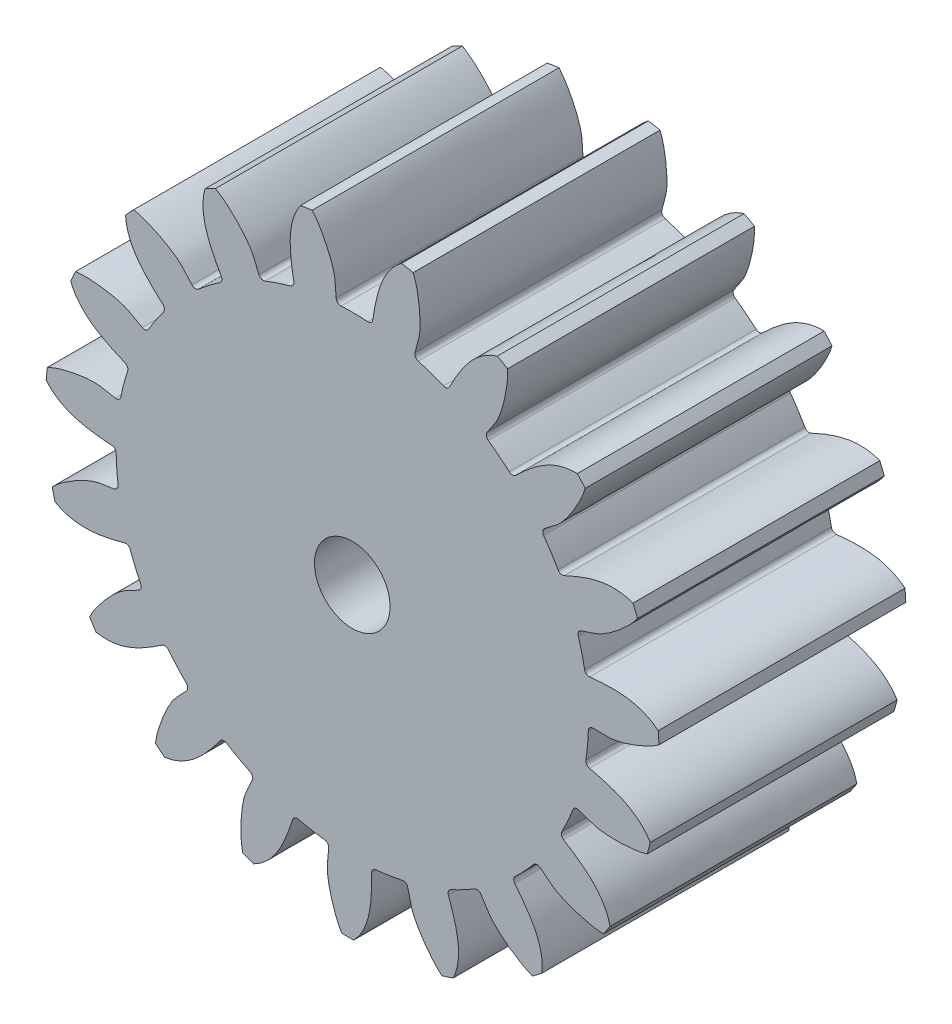
SolidWorks part; units mm, degrees
ref_plane "前视基准面" through (0, 0, 0) normal (0, 0, 1) x (1, 0, 0)
ref_plane "上视基准面" through (0, 0, 0) normal (0, 1, 0) x (1, 0, 0)
ref_plane "右视基准面" through (0, 0, 0) normal (1, 0, 0) x (0, 0, -1)
other "Configuration Table"
sketch "草图3" plane through (0, 0, 0) normal (0, 0, 1) x (1, 0, 0)
  circle A0 centre (0, 0) radius 13
  circle A1 centre (0, 0) radius 10
  dimension "D1" = 26
  dimension "D2" = 20
extrude "凸台-拉伸1" add sketch "草图3" along normal blind 4 contours A1 | A0 A1
sketch "草图6" plane through (0, 0, 4) normal (0, 0, 1) x (1, 0, 0)
  line L0 (0, 14.519) -> (0, -0.3622) construction
  line L5 (0, 0) -> (-1.6968, 12.8888) construction
  line L6 (-1.6968, 12.8888) -> (-1.8736, 14.2316)
  line L7 (-1.8736, 14.2316) -> (3.0009, 14.404)
  line L8 (3.0009, 14.404) -> (2.085, 12.8317)
  arc A0 (0.6559, 9.9785) -> (-0.4764, 9.9886) centre (0, 0) ccw
  circle A1 centre (0, 0) radius 13 construction
  arc A2 (0.6559, 9.9785) -> (0.8668, 10.1484) centre (0.669, 10.178) ccw
  arc A3 (-0.6854, 10.1744) -> (-0.4764, 9.9886) centre (-0.4859, 10.1884) ccw
  spline S0 degree 3 poles (-1.6968, 12.8888) (-1.3404, 12.4914) (-0.7219, 11.2236) (-0.7215, 10.6885) (-0.6854, 10.1744) knots 0 0 0 0 0.644244 0.940775 0.940775 0.940775 0.940775
  spline S1 degree 3 poles (2.085, 12.8317) (1.4718, 12.3854) (1.0735, 11.4242) (0.9081, 10.424) (0.8668, 10.1484) knots 0 0 0 0 0.67612 0.940775 0.940775 0.940775 0.940775
  dimension "D1" = 20
  dimension "D2" = 0.2
  dimension "D3" = 7.5
extrude "切除-拉伸2" cut sketch "草图6" against normal through all both
pattern_circular "阵列(圆周)4" count 19 every 18.947 about axis through (0, 0, 4) along (0, 0, 1) of "切除-拉伸2"
sketch "草图7" plane through (0, 0, 4) normal (0, 0, 1) x (1, 0, 0)
  circle A0 centre (0, 0) radius 12.5
  dimension "D1" = 25
ref_plane "基准面3" through (0, 0, 2) normal (0, 0, 1) x (1, 0, 0)
sketch "草图8" plane through (0, 0, 0) normal (0, 0, -1) x (-1, 0, 0)
  circle A5 centre (0, 0) radius 4.05
  dimension "D1" = 8.1
extrude "切除-拉伸4" cut sketch "草图8" against normal through all both
sketch "草图10" plane through (0, 0, 0) normal (0, 0, -1) x (-1, 0, 0)
  circle A0 centre (0, 0) radius 4.5
  dimension "D1" = 9
extrude "切除-拉伸5" cut sketch "草图10" against normal blind 0.6
sketch "草图11" plane through (0, 0, 4) normal (0, 0, 1) x (1, 0, 0)
  circle A0 centre (0, 0) radius 4.5
  dimension "D1" = 9
extrude "切除-拉伸6" cut sketch "草图11" against normal blind 0.6
sketch "草图13" plane through (0, 0, 4) normal (0, 0, 1) x (1, 0, 0)
  arc A61 (0.9955, -9.9503) -> (0.8154, -10.1526) centre (1.0154, -10.1493) ccw
  arc A62 (3.7951, -12.4337) -> (4.2735, -12.2775) centre (0, 0) ccw
  arc A63 (7.6267, -10.5277) -> (8.0285, -10.2247) centre (0, 0) ccw
  arc A64 (10.6318, -7.4809) -> (10.9134, -7.0638) centre (0, 0) ccw
  arc A65 (10.6318, -7.4809) -> (10.9134, -7.0638) centre (0, 0) ccw
  arc A66 (8.8746, -4.6089) -> (8.9454, -4.8703) centre (9.052, -4.7011) ccw
  arc A67 (8.8746, -4.6089) -> (8.9454, -4.8703) centre (9.052, -4.7011) ccw
  arc A68 (9.6948, 3.1621) -> (9.566, 2.9139) centre (9.7574, 2.9722) ccw
  arc A69 (12.0778, 4.8089) -> (11.8827, 5.2728) centre (0, 0) ccw
  arc A70 (8.7124, 4.9086) -> (8.97, 4.825) centre (8.8866, 5.0068) ccw
  arc A71 (8.7124, 4.9086) -> (8.1016, 5.8621) centre (0, 0) ccw
  arc A72 (8.1428, 6.1387) -> (8.1016, 5.8621) centre (8.2636, 5.9793) ccw
  arc A73 (9.862, 8.47) -> (9.5268, 8.8454) centre (0, 0) ccw
  arc A74 (6.6465, 7.4716) -> (6.9173, 7.4761) centre (6.7794, 7.621) ccw
  arc A75 (6.6465, 7.4716) -> (5.7592, 8.1751) centre (0, 0) ccw
  arc A76 (5.7084, 8.4501) -> (5.7592, 8.1751) centre (5.8744, 8.3386) ccw
  arc A77 (6.5774, 11.2133) -> (6.1385, 11.4595) centre (0, 0) ccw
  arc A78 (3.8603, 9.2248) -> (4.115, 9.3171) centre (3.9375, 9.4093) ccw
  arc A79 (3.8603, 9.2248) -> (2.7927, 9.6021) centre (0, 0) ccw
  arc A80 (2.6553, 9.8457) -> (2.7927, 9.6021) centre (2.8486, 9.7942) ccw
  arc A81 (2.5801, 12.7414) -> (2.085, 12.8317) centre (0, 0) ccw
  arc A82 (0.6559, 9.9785) -> (0.8668, 10.1484) centre (0.669, 10.178) ccw
  arc A83 (0.6559, 9.9785) -> (-0.4764, 9.9886) centre (0, 0) ccw
  arc A84 (-0.6854, 10.1744) -> (-0.4764, 9.9886) centre (-0.4859, 10.1884) ccw
  arc A85 (-1.6968, 12.8888) -> (-2.1944, 12.8134) centre (0, 0) ccw
  arc A86 (-2.6197, 9.6508) -> (-2.4754, 9.88) centre (-2.6721, 9.8438) ccw
  arc A87 (-2.6197, 9.6508) -> (-3.6939, 9.2927) centre (0, 0) ccw
  arc A88 (-3.9519, 9.4006) -> (-3.6939, 9.2927) centre (-3.7678, 9.4786) ccw
  arc A89 (-5.7899, 11.6395) -> (-6.236, 11.4067) centre (0, 0) ccw
  arc A90 (-5.6113, 8.2773) -> (-5.5493, 8.5409) centre (-5.7236, 8.4428) ccw
  arc A91 (-5.6113, 8.2773) -> (-6.5111, 7.5898) centre (0, 0) ccw
  arc A92 (-6.7902, 7.608) -> (-6.5111, 7.5898) centre (-6.6413, 7.7416) ccw
  arc A93 (-9.2555, 9.1288) -> (-9.6019, 8.7638) centre (0, 0) ccw
  arc A94 (-7.9949, 6.0068) -> (-8.0218, 6.2763) centre (-8.1548, 6.1269) ccw
  arc A95 (-7.9949, 6.0068) -> (-8.6227, 5.0644) centre (0, 0) ccw
  arc A96 (-8.8926, 4.9911) -> (-8.6227, 5.0644) centre (-8.7952, 5.1657) ccw
  arc A97 (-11.7181, 5.629) -> (-11.9272, 5.1712) centre (0, 0) ccw
  arc A98 (-9.5121, 3.0854) -> (-9.6251, 3.3315) centre (-9.7024, 3.1471) ccw
  arc A99 (-9.5121, 3.0854) -> (-9.7999, 1.9902) centre (0, 0) ccw
  arc A100 (-10.0314, 1.8332) -> (-9.7999, 1.9902) centre (-9.9959, 2.03) ccw
  arc A101 (-12.9109, 1.5191) -> (-12.9601, 1.0182) centre (0, 0) ccw
  arc A102 (-9.9985, -0.1704) -> (-10.1853, 0.0258) centre (-10.1985, -0.1738) ccw
  arc A103 (-9.9985, -0.1704) -> (-9.9152, -1.2996) centre (0, 0) ccw
  arc A104 (-10.0831, -1.5233) -> (-9.9152, -1.2996) centre (-10.1135, -1.3256) ccw
  arc A105 (-12.7046, -2.7554) -> (-12.5885, -3.2451) centre (0, 0) ccw
  arc A106 (-9.4015, -3.4077) -> (-9.6418, -3.2828) centre (-9.5895, -3.4758) ccw
  arc A107 (-9.4015, -3.4077) -> (-8.956, -4.4487) centre (0, 0) ccw
  arc A108 (-9.0421, -4.7147) -> (-8.956, -4.4487) centre (-9.1351, -4.5376) ccw
  arc A109 (-11.1216, -6.7313) -> (-10.8527, -7.1567) centre (0, 0) ccw
  arc A110 (-7.7856, -6.2757) -> (-8.0535, -6.2356) centre (-7.9413, -6.4012) ccw
  arc A111 (-7.7856, -6.2757) -> (-7.0262, -7.1156) centre (0, 0) ccw
  arc A112 (-7.0213, -7.3953) -> (-7.0262, -7.1156) centre (-7.1667, -7.2579) ccw
  arc A113 (-8.3333, -9.9777) -> (-7.9409, -10.2928) centre (0, 0) ccw
  arc A114 (-5.326, -8.4636) -> (-5.5924, -8.5127) centre (-5.4326, -8.6329) ccw
  arc A115 (-5.326, -8.4636) -> (-4.3351, -9.0115) centre (0, 0) ccw
  arc A116 (-4.2397, -9.2744) -> (-4.3351, -9.0115) centre (-4.4218, -9.1917) ccw
  arc A117 (-4.6421, -12.143) -> (-4.1686, -12.3135) centre (0, 0) ccw
  arc A118 (-2.2893, -9.7344) -> (-2.5253, -9.8673) centre (-2.3351, -9.9291) ccw
  arc A119 (-2.2893, -9.7344) -> (-1.1742, -9.9308) centre (0, 0) ccw
  arc A120 (-0.9986, -10.1485) -> (-1.1742, -9.9308) centre (-1.1976, -10.1294) ccw
  arc A121 (-0.4477, -12.9923) -> (0.0555, -12.9999) centre (0, 0) ccw
  arc A122 (0.9955, -9.9503) -> (0.8154, -10.1526) centre (1.0154, -10.1493) ccw
  arc A123 (3.7951, -12.4337) -> (4.2735, -12.2775) centre (0, 0) ccw
  arc A124 (7.6267, -10.5277) -> (8.0285, -10.2247) centre (0, 0) ccw
  arc A129 (9.6948, 3.1621) -> (9.566, 2.9139) centre (9.7574, 2.9722) ccw
  arc A130 (12.0778, 4.8089) -> (11.8827, 5.2728) centre (0, 0) ccw
  arc A131 (8.7124, 4.9086) -> (8.97, 4.825) centre (8.8866, 5.0068) ccw
  arc A132 (8.7124, 4.9086) -> (8.1016, 5.8621) centre (0, 0) ccw
  arc A133 (8.1428, 6.1387) -> (8.1016, 5.8621) centre (8.2636, 5.9793) ccw
  arc A134 (9.862, 8.47) -> (9.5268, 8.8454) centre (0, 0) ccw
  arc A135 (6.6465, 7.4716) -> (6.9173, 7.4761) centre (6.7794, 7.621) ccw
  arc A136 (6.6465, 7.4716) -> (5.7592, 8.1751) centre (0, 0) ccw
  arc A137 (5.7084, 8.4501) -> (5.7592, 8.1751) centre (5.8744, 8.3386) ccw
  arc A138 (6.5774, 11.2133) -> (6.1385, 11.4595) centre (0, 0) ccw
  arc A139 (3.8603, 9.2248) -> (4.115, 9.3171) centre (3.9375, 9.4093) ccw
  arc A140 (3.8603, 9.2248) -> (2.7927, 9.6021) centre (0, 0) ccw
  arc A141 (2.6553, 9.8457) -> (2.7927, 9.6021) centre (2.8486, 9.7942) ccw
  arc A142 (2.5801, 12.7414) -> (2.085, 12.8317) centre (0, 0) ccw
  arc A143 (0.6559, 9.9785) -> (0.8668, 10.1484) centre (0.669, 10.178) ccw
  arc A144 (0.6559, 9.9785) -> (-0.4764, 9.9886) centre (0, 0) ccw
  arc A145 (-0.6854, 10.1744) -> (-0.4764, 9.9886) centre (-0.4859, 10.1884) ccw
  arc A146 (-1.6968, 12.8888) -> (-2.1944, 12.8134) centre (0, 0) ccw
  arc A147 (-2.6197, 9.6508) -> (-2.4754, 9.88) centre (-2.6721, 9.8438) ccw
  arc A148 (-2.6197, 9.6508) -> (-3.6939, 9.2927) centre (0, 0) ccw
  arc A149 (-3.9519, 9.4006) -> (-3.6939, 9.2927) centre (-3.7678, 9.4786) ccw
  arc A150 (-5.7899, 11.6395) -> (-6.236, 11.4067) centre (0, 0) ccw
  arc A151 (-5.6113, 8.2773) -> (-5.5493, 8.5409) centre (-5.7236, 8.4428) ccw
  arc A152 (-5.6113, 8.2773) -> (-6.5111, 7.5898) centre (0, 0) ccw
  arc A153 (-6.7902, 7.608) -> (-6.5111, 7.5898) centre (-6.6413, 7.7416) ccw
  arc A154 (-9.2555, 9.1288) -> (-9.6019, 8.7638) centre (0, 0) ccw
  arc A155 (-7.9949, 6.0068) -> (-8.0218, 6.2763) centre (-8.1548, 6.1269) ccw
  arc A156 (-7.9949, 6.0068) -> (-8.6227, 5.0644) centre (0, 0) ccw
  arc A157 (-8.8926, 4.9911) -> (-8.6227, 5.0644) centre (-8.7952, 5.1657) ccw
  arc A158 (-11.7181, 5.629) -> (-11.9272, 5.1712) centre (0, 0) ccw
  arc A159 (-9.5121, 3.0854) -> (-9.6251, 3.3315) centre (-9.7024, 3.1471) ccw
  arc A160 (-9.5121, 3.0854) -> (-9.7999, 1.9902) centre (0, 0) ccw
  arc A161 (-10.0314, 1.8332) -> (-9.7999, 1.9902) centre (-9.9959, 2.03) ccw
  arc A162 (-12.9109, 1.5191) -> (-12.9601, 1.0182) centre (0, 0) ccw
  arc A163 (-9.9985, -0.1704) -> (-10.1853, 0.0258) centre (-10.1985, -0.1738) ccw
  arc A164 (-9.9985, -0.1704) -> (-9.9152, -1.2996) centre (0, 0) ccw
  arc A165 (-10.0831, -1.5233) -> (-9.9152, -1.2996) centre (-10.1135, -1.3256) ccw
  arc A166 (-12.7046, -2.7554) -> (-12.5885, -3.2451) centre (0, 0) ccw
  arc A167 (-9.4015, -3.4077) -> (-9.6418, -3.2828) centre (-9.5895, -3.4758) ccw
  arc A168 (-9.4015, -3.4077) -> (-8.956, -4.4487) centre (0, 0) ccw
  arc A169 (-9.0421, -4.7147) -> (-8.956, -4.4487) centre (-9.1351, -4.5376) ccw
  arc A170 (-11.1216, -6.7313) -> (-10.8527, -7.1567) centre (0, 0) ccw
  arc A171 (-7.7856, -6.2757) -> (-8.0535, -6.2356) centre (-7.9413, -6.4012) ccw
  arc A172 (-7.7856, -6.2757) -> (-7.0262, -7.1156) centre (0, 0) ccw
  arc A173 (-7.0213, -7.3953) -> (-7.0262, -7.1156) centre (-7.1667, -7.2579) ccw
  arc A174 (-8.3333, -9.9777) -> (-7.9409, -10.2928) centre (0, 0) ccw
  arc A175 (-5.326, -8.4636) -> (-5.5924, -8.5127) centre (-5.4326, -8.6329) ccw
  arc A176 (-5.326, -8.4636) -> (-4.3351, -9.0115) centre (0, 0) ccw
  arc A177 (-4.2397, -9.2744) -> (-4.3351, -9.0115) centre (-4.4218, -9.1917) ccw
  arc A178 (-4.6421, -12.143) -> (-4.1686, -12.3135) centre (0, 0) ccw
  arc A179 (-2.2893, -9.7344) -> (-2.5253, -9.8673) centre (-2.3351, -9.9291) ccw
  arc A180 (-2.2893, -9.7344) -> (-1.1742, -9.9308) centre (0, 0) ccw
  arc A181 (-0.9986, -10.1485) -> (-1.1742, -9.9308) centre (-1.1976, -10.1294) ccw
  arc A182 (-0.4477, -12.9923) -> (0.0555, -12.9999) centre (0, 0) ccw
  arc A198 (8.8746, -4.6089) -> (9.3387, -3.5761) centre (0, 0) ccw
  arc A199 (8.8746, -4.6089) -> (9.3387, -3.5761) centre (0, 0) ccw
  arc A200 (9.5928, -3.4593) -> (9.3387, -3.5761) centre (9.5255, -3.6476) ccw
  arc A201 (9.5928, -3.4593) -> (9.3387, -3.5761) centre (9.5255, -3.6476) ccw
  arc A202 (12.4848, -3.6234) -> (12.6157, -3.1375) centre (0, 0) ccw
  arc A203 (12.4848, -3.6234) -> (12.6157, -3.1375) centre (0, 0) ccw
  arc A204 (9.8902, -1.4776) -> (10.0421, -1.7019) centre (10.088, -1.5072) ccw
  arc A205 (9.8902, -1.4776) -> (10.0421, -1.7019) centre (10.088, -1.5072) ccw
  arc A206 (9.8902, -1.4776) -> (9.9939, -0.3501) centre (0, 0) ccw
  arc A207 (9.8902, -1.4776) -> (9.9939, -0.3501) centre (0, 0) ccw
  arc A208 (10.1963, -0.1571) -> (9.9939, -0.3501) centre (10.1937, -0.3571) ccw
  arc A209 (10.1963, -0.1571) -> (9.9939, -0.3501) centre (10.1937, -0.3571) ccw
  arc A210 (12.9849, 0.6267) -> (12.9509, 1.1288) centre (0, 0) ccw
  arc A211 (12.9849, 0.6267) -> (12.9509, 1.1288) centre (0, 0) ccw
  arc A212 (9.8341, 1.8138) -> (10.0506, 1.651) centre (10.0308, 1.85) ccw
  arc A213 (9.8341, 1.8138) -> (10.0506, 1.651) centre (10.0308, 1.85) ccw
  arc A214 (9.8341, 1.8138) -> (9.566, 2.9139) centre (0, 0) ccw
  arc A215 (9.8341, 1.8138) -> (9.566, 2.9139) centre (0, 0) ccw
  arc A216 (0.9955, -9.9503) -> (2.114, -9.774) centre (0, 0) ccw
  arc A217 (0.9955, -9.9503) -> (2.114, -9.774) centre (0, 0) ccw
  arc A218 (2.3508, -9.9228) -> (2.114, -9.774) centre (2.1563, -9.9695) ccw
  arc A219 (2.3508, -9.9228) -> (2.114, -9.774) centre (2.1563, -9.9695) ccw
  arc A220 (4.1724, -9.088) -> (4.0678, -9.3378) centre (4.2559, -9.2697) ccw
  arc A221 (4.1724, -9.088) -> (4.0678, -9.3378) centre (4.2559, -9.2697) ccw
  arc A222 (4.1724, -9.088) -> (5.1731, -8.558) centre (0, 0) ccw
  arc A223 (4.1724, -9.088) -> (5.1731, -8.558) centre (0, 0) ccw
  arc A224 (5.4453, -8.6219) -> (5.1731, -8.558) centre (5.2765, -8.7292) ccw
  arc A225 (5.4453, -8.6219) -> (5.1731, -8.558) centre (5.2765, -8.7292) ccw
  arc A226 (6.8972, -7.2408) -> (6.8794, -7.511) centre (7.0351, -7.3856) ccw
  arc A227 (6.8972, -7.2408) -> (6.8794, -7.511) centre (7.0351, -7.3856) ccw
  arc A228 (6.8972, -7.2408) -> (7.6715, -6.4146) centre (0, 0) ccw
  arc A229 (6.8972, -7.2408) -> (7.6715, -6.4146) centre (0, 0) ccw
  arc A230 (7.9498, -6.3867) -> (7.6715, -6.4146) centre (7.825, -6.5429) ccw
  arc A231 (7.9498, -6.3867) -> (7.6715, -6.4146) centre (7.825, -6.5429) ccw
  spline S31 degree 3 poles (-731.5328, 1850.5138) (19.8543, -20.677) (-32.4011, 17.1172) (72.329, -78.5631) (-1032.4895, 1698.0412) knots -4.705235 -4.705235 -4.705235 -4.705235 0.296531 9.087902 9.087902 9.087902 9.087902 only from (2.3508, -9.9228) to (3.7951, -12.4337)
  spline S32 degree 3 poles (-1919.6578, 532.6232) (-27.8786, -49.6134) (46.8106, 5.6607) (-49.9844, 2.209) (1993.0973, -217.6497) knots -11.806964 -11.806964 -11.806964 -11.806964 0.67612 14.264014 14.264014 14.264014 14.264014 only from (4.2735, -12.2775) to (4.0678, -9.3378)
  spline S33 degree 3 poles (-1292.7572, 1512.7195) (25.4924, -13.11) (-36.2034, 5.6691) (93.9194, -50.8212) (-1527.8994, 1270.7879) knots -4.705235 -4.705235 -4.705235 -4.705235 0.296531 9.087902 9.087902 9.087902 9.087902 only from (5.4453, -8.6219) to (7.6267, -10.5277)
  spline S34 degree 3 poles (-1783.7839, -881.8485) (18.9669, 21.494) (-14.3831, -33.7039) (72.3219, 78.5696) (-1606.9792, -1169.1861) knots -4.705235 -4.705235 -4.705235 -4.705235 0.296531 9.087902 9.087902 9.087902 9.087902 only from (9.6948, 3.1621) to (12.0778, 4.8089)
  spline S35 degree 3 poles (-372.2799, -1957.0849) (51.7462, -23.6864) (-9.507, 46.1833) (1.9262, -49.9961) (52.3177, 2004.2632) knots -11.806964 -11.806964 -11.806964 -11.806964 0.67612 14.264014 14.264014 14.264014 14.264014 only from (11.8827, 5.2728) to (8.97, 4.825)
  spline S36 degree 3 poles (-1400.7978, -1413.2612) (10.9601, 26.4879) (-2.6601, -36.5479) (42.8918, 97.7954) (-1140.2745, -1627.6217) knots -4.705235 -4.705235 -4.705235 -4.705235 0.296531 9.087902 9.087902 9.087902 9.087902 only from (8.1428, 6.1387) to (9.862, 8.47)
  spline S37 degree 3 poles (283.3557, -1971.9237) (56.6334, -5.601) (-23.9876, 40.594) (18.0555, -46.6618) (-601.3002, 1912.6542) knots -11.806964 -11.806964 -11.806964 -11.806964 0.67612 14.264014 14.264014 14.264014 14.264014 only from (9.5268, 8.8454) to (6.9173, 7.4761)
  spline S38 degree 3 poles (-866.0135, -1791.5251) (1.7656, 28.6115) (9.3511, -35.4314) (8.8137, 106.4235) (-550.0034, -1909.6792) knots -4.705235 -4.705235 -4.705235 -4.705235 0.296531 9.087902 9.087902 9.087902 9.087902 only from (5.7084, 8.4501) to (6.5774, 11.2133)
  spline S39 degree 3 poles (908.2853, -1773.074) (55.3835, 13.0913) (-35.8687, 30.6058) (32.2283, -38.2709) (-1189.7579, 1613.7795) knots -11.806964 -11.806964 -11.806964 -11.806964 0.67612 14.264014 14.264014 14.264014 14.264014 only from (6.1385, 11.4595) to (4.115, 9.3171)
  spline S40 degree 3 poles (-237.3833, -1975.6495) (-7.6202, 27.6345) (20.349, -30.4753) (-26.2195, 103.519) (99.8691, -1984.7933) knots -4.705235 -4.705235 -4.705235 -4.705235 0.296531 9.087902 9.087902 9.087902 9.087902 only from (2.6553, 9.8457) to (2.5801, 12.7414)
  spline S41 degree 3 poles (1434.7881, -1382.0843) (48.1319, 30.3649) (-43.8629, 17.3009) (42.9086, -25.7327) (-1649.2869, 1140.0267) knots -11.806964 -11.806964 -11.806964 -11.806964 0.67612 14.264014 14.264014 14.264014 14.264014 only from (2.085, 12.8317) to (0.8668, 10.1484)
  spline S42 degree 3 poles (416.9711, -1945.6816) (-16.1802, 23.6629) (29.1418, -22.2168) (-58.4114, 89.3966) (738.9193, -1844.8243) knots -4.705235 -4.705235 -4.705235 -4.705235 0.296531 9.087902 9.087902 9.087902 9.087902 only from (-0.6854, 10.1744) to (-1.6968, 12.8888)
  spline S43 degree 3 poles (1805.8093, -841.3242) (35.6645, 44.3481) (-47.1039, 2.1212) (48.9391, -10.4061) (-1930.0901, 542.7343) knots -11.806964 -11.806964 -11.806964 -11.806964 0.67612 14.264014 14.264014 14.264014 14.264014 only from (-2.1944, 12.8134) to (-2.4754, 9.88)
  spline S44 degree 3 poles (1026.1402, -1704.8689) (-22.9869, 17.1271) (34.7766, -11.5507) (-84.2736, 65.5867) (1297.8961, -1504.9399) knots -4.705235 -4.705235 -4.705235 -4.705235 0.296531 9.087902 9.087902 9.087902 9.087902 only from (-3.9519, 9.4006) to (-5.7899, 11.6395)
  spline S45 degree 3 poles (1981.1431, -209.3936) (19.3323, 53.5254) (-45.2404, -13.2883) (49.6663, 6.0482) (-2001.738, -113.3717) knots -11.806964 -11.806964 -11.806964 -11.806964 0.67612 14.264014 14.264014 14.264014 14.264014 only from (-6.236, 11.4067) to (-5.5493, 8.5409)
  spline S46 degree 3 poles (1524.1111, -1279.3072) (-27.3026, 8.7353) (36.6428, 0.3671) (-101.0033, 34.6694) (1716.2257, -1001.972) knots -4.705235 -4.705235 -4.705235 -4.705235 0.296531 9.087902 9.087902 9.087902 9.087902 only from (-6.7902, 7.608) to (-9.2555, 9.1288)
  spline S47 degree 3 poles (1941.7893, 445.228) (0.9051, 56.9025) (-38.4745, -27.2579) (45.0114, 21.8472) (-1856.4666, -757.1922) knots -11.806964 -11.806964 -11.806964 -11.806964 0.67612 14.264014 14.264014 14.264014 14.264014 only from (-9.6019, 8.7638) to (-8.0218, 6.2763)
  spline S48 degree 3 poles (1856.921, -715.1127) (-28.6596, -0.6031) (34.5382, 12.2451) (-106.7879, -0.0048) (1948.5756, -390.4248) knots -4.705235 -4.705235 -4.705235 -4.705235 0.296531 9.087902 9.087902 9.087902 9.087902 only from (-8.8926, 4.9911) to (-11.7181, 5.629)
  spline S49 degree 3 poles (1692.0125, 1051.6023) (-17.6201, 54.1132) (-27.5392, -38.2736) (35.4788, 35.2786) (-1510.0182, -1318.9592) knots -11.806964 -11.806964 -11.806964 -11.806964 0.67612 14.264014 14.264014 14.264014 14.264014 only from (-11.9272, 5.1712) to (-9.6251, 3.3315)
  spline S50 degree 3 poles (1988.5046, -73.4247) (-26.9109, -9.8762) (28.6908, 22.7962) (-101.0002, -34.6785) (1969.7671, 263.4309) knots -4.705235 -4.705235 -4.705235 -4.705235 0.296531 9.087902 9.087902 9.087902 9.087902 only from (-10.0314, 1.8332) to (-12.9109, 1.5191)
  spline S51 degree 3 poles (1258.8799, 1544.0191) (-34.2359, 45.46) (-13.6196, -45.1418) (22.1015, 44.887) (-999.9359, -1737.7964) knots -11.806964 -11.806964 -11.806964 -11.806964 0.67612 14.264014 14.264014 14.264014 14.264014 only from (-12.9601, 1.0182) to (-10.1853, 0.0258)
  spline S52 degree 3 poles (1904.6029, 576.2201) (-22.246, -18.079) (19.7344, 30.8769) (-84.2677, -65.5942) (1777.5038, 888.7399) knots -4.705235 -4.705235 -4.705235 -4.705235 0.296531 9.087902 9.087902 9.087902 9.087902 only from (-10.0831, -1.5233) to (-12.7046, -2.7554)
  spline S53 degree 3 poles (689.3281, 1869.1176) (-47.1418, 31.8805) (1.7758, -47.1182) (6.3292, 49.6313) (-381.495, -1968.3165) knots -11.806964 -11.806964 -11.806964 -11.806964 0.67612 14.264014 14.264014 14.264014 14.264014 only from (-12.5885, -3.2451) to (-9.6418, -3.2828)
  spline S54 degree 3 poles (1614.3079, 1163.4224) (-15.1704, -24.3227) (8.6394, 35.6116) (-58.4034, -89.4018) (1392.6204, 1417.74) knots -4.705235 -4.705235 -4.705235 -4.705235 0.296531 9.087902 9.087902 9.087902 9.087902 only from (-9.0421, -4.7147) to (-11.1216, -6.7313)
  spline S55 degree 3 poles (45.0769, 1991.6681) (-54.9391, 14.8462) (16.9789, -43.9886) (-10.129, 48.9972) (278.2867, -1985.5389) knots -11.806964 -11.806964 -11.806964 -11.806964 0.67612 14.264014 14.264014 14.264014 14.264014 only from (-10.8527, -7.1567) to (-8.0535, -6.2356)
  spline S56 degree 3 poles (1149.0776, 1624.5499) (-6.4508, -27.9307) (-3.3918, 36.4873) (-26.2102, -103.5214) (856.8249, 1793.1061) knots -4.705235 -4.705235 -4.705235 -4.705235 0.296531 9.087902 9.087902 9.087902 9.087902 only from (-7.0213, -7.3953) to (-8.3333, -9.9777)
  spline S57 degree 3 poles (-604.059, 1898.3905) (-56.7829, -3.7969) (30.342, -36.0921) (-25.4895, 43.0535) (907.9118, -1787.5973) knots -11.806964 -11.806964 -11.806964 -11.806964 0.67612 14.264014 14.264014 14.264014 14.264014 only from (-7.9409, -10.2928) to (-5.5924, -8.5127)
  spline S58 degree 3 poles (559.3269, 1909.6322) (2.9678, -28.5119) (-15.0554, 33.409) (8.8232, -106.4227) (228.1792, 1974.1613) knots -4.705235 -4.705235 -4.705235 -4.705235 0.296531 9.087902 9.087902 9.087902 9.087902 only from (-4.2397, -9.2744) to (-4.6421, -12.143)
  spline S59 degree 3 poles (-1187.7358, 1599.3928) (-52.4733, -22.0285) (40.417, -24.2845) (-38.0879, 32.4443) (1439.1506, -1395.9419) knots -11.806964 -11.806964 -11.806964 -11.806964 0.67612 14.264014 14.264014 14.264014 14.264014 only from (-4.1686, -12.3135) to (-2.5253, -9.8673)
  spline S60 degree 3 poles (-91.0355, 1987.7762) (12.0648, -26.0034) (-25.0876, 26.7103) (42.9006, -97.7916) (-425.1933, 1941.2854) knots -4.705235 -4.705235 -4.705235 -4.705235 0.296531 9.087902 9.087902 9.087902 9.087902 only from (-0.9986, -10.1485) to (-0.4477, -12.9923)
  spline S61 degree 3 poles (-1642.703, 1127.0761) (-42.4775, -37.8731) (46.1123, -9.8454) (-46.5588, 18.3193) (1814.435, -853.0145) knots -11.806964 -11.806964 -11.806964 -11.806964 0.67612 14.264014 14.264014 14.264014 14.264014 only from (0.0555, -12.9999) to (0.8154, -10.1526)
  spline S62 degree 3 poles (2.3508, -9.9228) (2.4709, -10.4239) (2.5593, -10.9517) (3.3781, -12.1004) (3.7951, -12.4337) knots 0 0 0 0 0.296531 0.940775 0.940775 0.940775 0.940775
  spline S63 degree 3 poles (4.2735, -12.2775) (4.6004, -11.5931) (4.4932, -10.5582) (4.1626, -9.5998) (4.0678, -9.3378) knots 0 0 0 0 0.67612 0.940775 0.940775 0.940775 0.940775
  spline S64 degree 3 poles (5.4453, -8.6219) (5.7217, -9.0568) (5.9767, -9.5273) (7.1241, -10.3479) (7.6267, -10.5277) knots 0 0 0 0 0.296531 0.940775 0.940775 0.940775 0.940775
  spline S65 degree 3 poles (9.6948, 3.1621) (10.1843, 3.3233) (10.7029, 3.455) (11.7801, 4.3658) (12.0778, 4.8089) knots 0 0 0 0 0.296531 0.940775 0.940775 0.940775 0.940775
  spline S66 degree 3 poles (11.8827, 5.2728) (11.1736, 5.5421) (10.1511, 5.3497) (9.2233, 4.9412) (8.97, 4.825) knots 0 0 0 0 0.67612 0.940775 0.940775 0.940775 0.940775
  spline S67 degree 3 poles (8.1428, 6.1387) (8.5534, 6.45) (9.0012, 6.743) (9.7242, 7.9542) (9.862, 8.47) knots 0 0 0 0 0.296531 0.940775 0.940775 0.940775 0.940775
  spline S68 degree 3 poles (9.5268, 8.8454) (8.7687, 8.8699) (7.8641, 8.3559) (7.1192, 7.6683) (6.9173, 7.4761) knots 0 0 0 0 0.67612 0.940775 0.940775 0.940775 0.940775
  spline S69 degree 3 poles (5.7084, 8.4501) (5.9956, 8.8778) (6.324, 9.3003) (6.6146, 10.6807) (6.5774, 11.2133) knots 0 0 0 0 0.296531 0.940775 0.940775 0.940775 0.940775
  spline S70 degree 3 poles (6.1385, 11.4595) (5.4135, 11.2365) (4.7248, 10.4567) (4.2436, 9.5644) (4.115, 9.3171) knots 0 0 0 0 0.67612 0.940775 0.940775 0.940775 0.940775
  spline S71 degree 3 poles (2.6553, 9.8457) (2.7881, 10.3436) (2.9615, 10.8498) (2.7882, 12.2498) (2.5801, 12.7414) knots 0 0 0 0 0.296531 0.940775 0.940775 0.940775 0.940775
  spline S72 degree 3 poles (2.085, 12.8317) (1.4718, 12.3854) (1.0735, 11.4242) (0.9081, 10.424) (0.8668, 10.1484) knots 0 0 0 0 0.67612 0.940775 0.940775 0.940775 0.940775
  spline S73 degree 3 poles (-0.6854, 10.1744) (-0.7215, 10.6885) (-0.7219, 11.2236) (-1.3404, 12.4914) (-1.6968, 12.8888) knots 0 0 0 0 0.296531 0.940775 0.940775 0.940775 0.940775
  spline S74 degree 3 poles (-2.1944, 12.8134) (-2.6295, 12.1922) (-2.6941, 11.1538) (-2.5258, 10.1541) (-2.4754, 9.88) knots 0 0 0 0 0.67612 0.940775 0.940775 0.940775 0.940775
  spline S75 degree 3 poles (-3.9519, 9.4006) (-4.1529, 9.8751) (-4.327, 10.3811) (-5.3237, 11.3793) (-5.7899, 11.6395) knots 0 0 0 0 0.296531 0.940775 0.940775 0.940775 0.940775
  spline S76 degree 3 poles (-6.236, 11.4067) (-6.4459, 10.6778) (-6.1697, 9.6747) (-5.6859, 8.7838) (-5.5493, 8.5409) knots 0 0 0 0 0.67612 0.940775 0.940775 0.940775 0.940775
  spline S77 degree 3 poles (-6.7902, 7.608) (-7.1343, 7.9916) (-7.4633, 8.4136) (-8.7301, 9.0342) (-9.2555, 9.1288) knots 0 0 0 0 0.296531 0.940775 0.940775 0.940775 0.940775
  spline S78 degree 3 poles (-9.6019, 8.7638) (-9.5637, 8.0063) (-8.9768, 7.1472) (-8.23, 6.4616) (-8.0218, 6.2763) knots 0 0 0 0 0.67612 0.940775 0.940775 0.940775 0.940775
  spline S79 degree 3 poles (-8.8926, 4.9911) (-9.3426, 5.242) (-9.7908, 5.5344) (-11.1905, 5.71) (-11.7181, 5.629) knots 0 0 0 0 0.296531 0.940775 0.940775 0.940775 0.940775
  spline S80 degree 3 poles (-11.9272, 5.1712) (-11.6451, 4.4672) (-10.8111, 3.8452) (-9.8821, 3.4392) (-9.6251, 3.3315) knots 0 0 0 0 0.67612 0.940775 0.940775 0.940775 0.940775
  spline S81 degree 3 poles (-10.0314, 1.8332) (-10.5385, 1.9245) (-11.0573, 2.0555) (-12.4382, 1.7671) (-12.9109, 1.5191) knots 0 0 0 0 0.296531 0.940775 0.940775 0.940775 0.940775
  spline S82 degree 3 poles (-12.9601, 1.0182) (-12.4646, 0.4439) (-11.4739, 0.1265) (-10.4634, 0.0442) (-10.1853, 0.0258) knots 0 0 0 0 0.67612 0.940775 0.940775 0.940775 0.940775
  spline S83 degree 3 poles (-10.0831, -1.5233) (-10.5924, -1.6017) (-11.1256, -1.6462) (-12.338, -2.3673) (-12.7046, -2.7554) knots 0 0 0 0 0.296531 0.940775 0.940775 0.940775 0.940775
  spline S84 degree 3 poles (-12.5885, -3.2451) (-11.9334, -3.6274) (-10.8932, -3.6059) (-9.9108, -3.3557) (-9.6418, -3.2828) knots 0 0 0 0 0.67612 0.940775 0.940775 0.940775 0.940775
  spline S85 degree 3 poles (-9.0421, -4.7147) (-9.4984, -4.9542) (-9.9883, -5.1695) (-10.9008, -6.2452) (-11.1216, -6.7313) knots 0 0 0 0 0.296531 0.940775 0.940775 0.940775 0.940775
  spline S86 degree 3 poles (-10.8527, -7.1567) (-10.109, -7.3056) (-9.1322, -6.9476) (-8.2842, -6.3919) (-8.0535, -6.2356) knots 0 0 0 0 0.67612 0.940775 0.940775 0.940775 0.940775
  spline S87 degree 3 poles (-7.0213, -7.3953) (-7.3751, -7.7699) (-7.7686, -8.1326) (-8.2824, -9.4463) (-8.3333, -9.9777) knots 0 0 0 0 0.296531 0.940775 0.940775 0.940775 0.940775
  spline S88 degree 3 poles (-7.9409, -10.2928) (-7.1892, -10.1922) (-6.3815, -9.5364) (-5.7599, -8.7354) (-5.5924, -8.5127) knots 0 0 0 0 0.67612 0.940775 0.940775 0.940775 0.940775
  spline S89 degree 3 poles (-4.2397, -9.2744) (-4.4526, -9.7436) (-4.707, -10.2144) (-4.7664, -11.6238) (-4.6421, -12.143) knots 0 0 0 0 0.296531 0.940775 0.940775 0.940775 0.940775
  spline S90 degree 3 poles (-4.1686, -12.3135) (-3.4902, -11.9742) (-2.9393, -11.0917) (-2.6114, -10.1324) (-2.5253, -9.8673) knots 0 0 0 0 0.67612 0.940775 0.940775 0.940775 0.940775
  spline S91 degree 3 poles (-0.9986, -10.1485) (-1.0476, -10.6614) (-1.1353, -11.1893) (-0.7339, -12.5416) (-0.4477, -12.9923) knots 0 0 0 0 0.296531 0.940775 0.940775 0.940775 0.940775
  spline S92 degree 3 poles (0.0555, -12.9999) (0.5869, -12.4587) (0.8215, -11.4451) (0.82, -10.4313) (0.8154, -10.1526) knots 0 0 0 0 0.67612 0.940775 0.940775 0.940775 0.940775
  spline S100 degree 3 poles (-989.2957, -83.3185) (-1.1721, -41.8195) (29.4009, 10.2514) (-30.6479, -8.1015) (980.5736, 220.3024) knots -9.207047 -9.207047 -9.207047 -9.207047 0.67612 11.538096 11.538096 11.538096 11.538096 only from (8.0285, -10.2247) to (6.8794, -7.511)
  spline S101 degree 3 poles (8.0285, -10.2247) (8.1155, -9.4712) (7.678, -8.5272) (7.0542, -7.7281) (6.8794, -7.511) knots 0 0 0 0 0.67612 0.940775 0.940775 0.940775 0.940775
  spline S102 degree 3 poles (-850.5561, 506.4134) (19.9341, -4.5085) (-19.4118, -6.8549) (73.0652, -14.9052) (-920.2791, 357.7386) knots -3.681392 -3.681392 -3.681392 -3.681392 0.296531 7.356012 7.356012 7.356012 7.356012 only from (7.9498, -6.3867) to (10.6318, -7.4809)
  spline S103 degree 3 poles (7.9498, -6.3867) (8.3524, -6.7083) (8.7464, -7.0704) (10.098, -7.474) (10.6318, -7.4809) knots 0 0 0 0 0.296531 0.940775 0.940775 0.940775 0.940775
  spline S104 degree 3 poles (-908.6395, -400.0279) (12.4702, -39.9342) (24.4792, 19.2424) (-26.3567, -17.6139) (855.9114, 526.7576) knots -9.207047 -9.207047 -9.207047 -9.207047 0.67612 11.538096 11.538096 11.538096 11.538096 only from (10.9134, -7.0638) to (8.9454, -4.8703)
  spline S105 degree 3 poles (10.9134, -7.0638) (10.751, -6.323) (10.0308, -5.5722) (9.1813, -5.0189) (8.9454, -4.8703) knots 0 0 0 0 0.67612 0.940775 0.940775 0.940775 0.940775
  spline S106 degree 3 poles (-968.9028, 202.7994) (20.318, 2.2084) (-16.1342, -12.7865) (73.9461, 9.6267) (-986.5734, 39.5412) knots -3.681392 -3.681392 -3.681392 -3.681392 0.296531 7.356012 7.356012 7.356012 7.356012 only from (9.5928, -3.4593) to (12.4848, -3.6234)
  spline S107 degree 3 poles (9.5928, -3.4593) (10.078, -3.6328) (10.5682, -3.8474) (11.9777, -3.7902) (12.4848, -3.6234) knots 0 0 0 0 0.296531 0.940775 0.940775 0.940775 0.940775
  spline S108 degree 3 poles (-729.518, -673.388) (24.7612, -33.7214) (16.9049, 26.1482) (-19.2094, -25.2175) (638.4978, 776.1303) knots -9.207047 -9.207047 -9.207047 -9.207047 0.67612 11.538096 11.538096 11.538096 11.538096 only from (12.6157, -3.1375) to (10.0421, -1.7019)
  spline S109 degree 3 poles (12.6157, -3.1375) (12.2216, -2.4895) (11.2966, -2.0133) (10.3134, -1.7658) (10.0421, -1.7019) knots 0 0 0 0 0.67612 0.940775 0.940775 0.940775 0.940775
  spline S110 degree 3 poles (-982.2538, -122.791) (18.5, 8.6859) (-11.1083, -17.3325) (66.8137, 33.1153) (-945.9571, -282.9411) knots -3.681392 -3.681392 -3.681392 -3.681392 0.296531 7.356012 7.356012 7.356012 7.356012 only from (10.1963, -0.1571) to (12.9849, 0.6267)
  spline S111 degree 3 poles (10.1963, -0.1571) (10.7115, -0.1636) (11.2449, -0.2074) (12.5594, 0.3043) (12.9849, 0.6267) knots 0 0 0 0 0.296531 0.940775 0.940775 0.940775 0.940775
  spline S112 degree 3 poles (-471.342, -873.7761) (34.3689, -23.8543) (7.4986, 30.2204) (-9.9805, -30.0884) (351.8931, 941.3974) knots -9.207047 -9.207047 -9.207047 -9.207047 0.67612 11.538096 11.538096 11.538096 11.538096 only from (12.9509, 1.1288) to (10.0506, 1.651)
  spline S113 degree 3 poles (12.9509, 1.1288) (12.3677, 1.6137) (11.3382, 1.7638) (10.328, 1.6786) (10.0506, 1.651) knots 0 0 0 0 0.67612 0.940775 0.940775 0.940775 0.940775
  dimension "D1" = 0
extrude "凸台-拉伸4" add sketch "草图13" along normal blind 6.45
sketch "草图14" plane through (0, 0, 4) normal (0, 0, -1) x (-1, 0, 0)
  circle A0 centre (0, 0) radius 1.6
  dimension "D1" = 3.2
extrude "切除-拉伸7" cut sketch "草图14" against normal through all both and the other way through all
